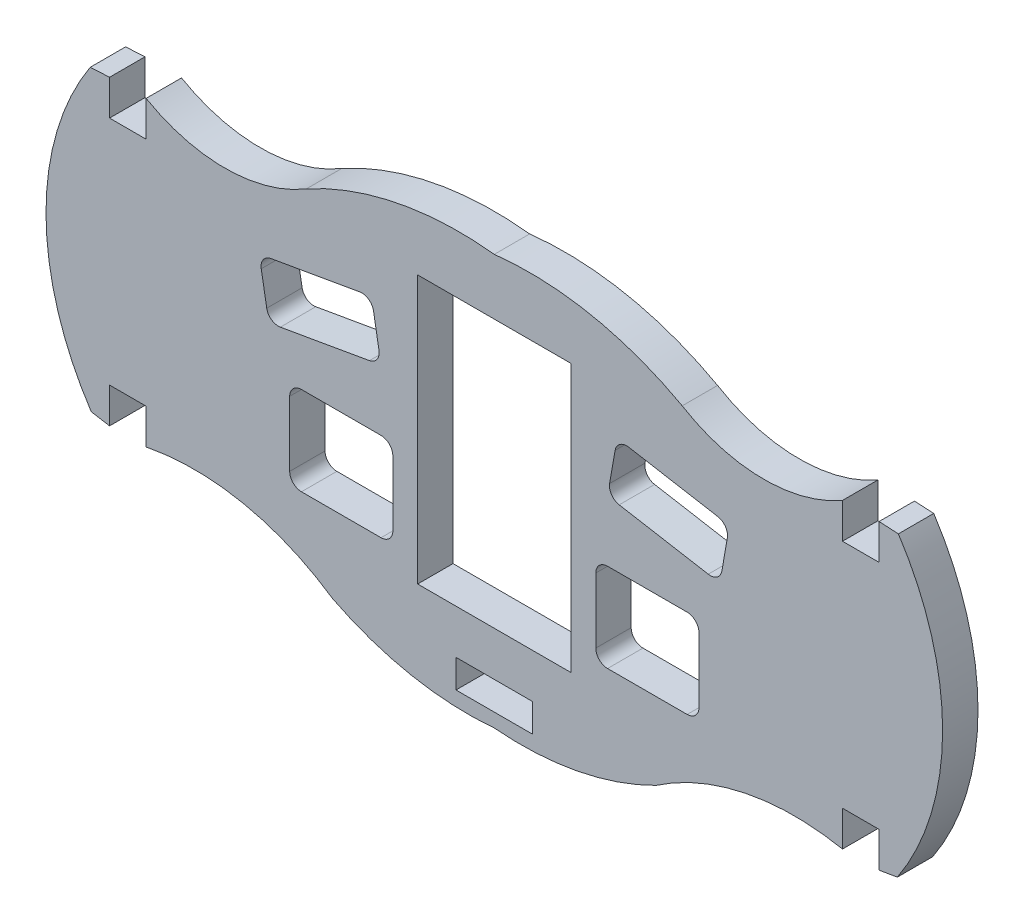
SolidWorks part; units mm, degrees
ref_plane "Front Plane" through (0, 0, 0) normal (0, 0, 1) x (1, 0, 0)
ref_plane "Top Plane" through (0, 0, 0) normal (0, 1, 0) x (1, 0, 0)
ref_plane "Right Plane" through (0, 0, 0) normal (1, 0, 0) x (0, 0, -1)
sketch "Sketch1" plane through (0, 0, 0) normal (0, 0, 1) x (1, 0, 0)
  line L0 (-29.524, 0) -> (29.524, 0) construction
  line L1 (-29.524, -12.802) -> (-29.524, 12.802)
  line L2 (0, 33.6392) -> (0, -30.2413) construction
  line L3 (29.524, -12.802) -> (29.524, 12.802)
  line L4 (-29.524, 9.802) -> (-32.624, 9.802)
  line L5 (-32.624, 9.802) -> (-32.624, 12.802)
  line L6 (-32.624, -9.802) -> (-32.624, -12.802)
  line L7 (-29.524, -9.802) -> (-32.624, -9.802)
  line L8 (32.624, -9.802) -> (32.624, -12.802)
  line L9 (29.524, -9.802) -> (32.624, -9.802)
  line L10 (32.624, 9.802) -> (32.624, 12.802)
  line L11 (29.524, 9.802) -> (32.624, 9.802)
  line L12 (-32.624, -12.802) -> (-34.1749, -12.5392)
  line L13 (-32.624, 12.802) -> (-34.2627, 12.7145)
  line L14 (32.624, -12.802) -> (34.1749, -12.5392)
  line L15 (32.624, 12.802) -> (34.2627, 12.7145)
  line L16 (0, 0) -> (2.992, -10.57) construction
  line L17 (0, 0) -> (-2.992, -10.57) construction
  line L18 (0, 0) -> (2.243, 6.575) construction
  line L19 (0, 0) -> (-2.243, 6.575) construction
  line L20 (0, 0) -> (-16.59, 12.577) construction
  line L21 (0, 0) -> (16.59, 12.577) construction
  line L22 (0, 0) -> (16.293, -14.525) construction
  line L23 (0, 0) -> (-16.293, -14.525) construction
  arc A0 (-34.2627, 12.7145) -> (-34.1749, -12.5392) centre (-15.1087, 0.1541) ccw
  arc A1 (34.2627, 12.7145) -> (34.1749, -12.5392) centre (15.1087, 0.1541) cw
  arc A2 (-29.524, 12.802) -> (-15.9318, 12.9517) centre (-22.8542, 24.3468) ccw
  arc A3 (0, 16.1087) -> (-27.048, 1.347) centre (-2.992, -10.57) ccw
  arc A4 (0, -18.6756) -> (27.048, 1.347) centre (2.243, 6.575) ccw
  arc A5 (27.048, 1.347) -> (0, 16.1087) centre (2.992, -10.57) ccw
  arc A6 (29.524, 12.802) -> (15.9318, 12.9517) centre (22.8542, 24.3468) cw
  arc A7 (-27.048, 1.347) -> (0, -18.6756) centre (-2.243, 6.575) ccw
  arc A8 (-13.7026, -16.037) -> (-29.524, -12.802) centre (-25.4515, -33.1913) ccw
  arc A9 (13.7026, -16.037) -> (29.524, -12.802) centre (25.4515, -33.1913) cw
  point P4 (0, 0)
  point P7 (-29.524, 0)
  dimension "D10" = 45.81
  dimension "D13" = 53.692
  dimension "D14" = 6.575
  dimension "D16" = 12.577
  dimension "D17" = 50.7
  dimension "D19" = 26.666
  dimension "D22" = 41.584
  dimension "D1" = 59.048
  dimension "D2" = 25.604
  dimension "D3" = 3
  dimension "D4" = 3.1
  dimension "D5" = 3
  dimension "D6" = 1.573
  dimension "D7" = 80.384
  dimension "D8" = 1.641
  dimension "D9" = 86.945
  dimension "D11" = 10.57
  dimension "D12" = 2.992
  dimension "D15" = 2.243
  dimension "D18" = 16.59
  dimension "D20" = 14.525
  dimension "D21" = 16.293
extrude "Boss-Extrude1" add sketch "Sketch1" against normal blind 3 contours A4 A9 A5 A6 A3 A2 A7 A8 | A1 L15 L10 L11 L3 L9 L8 L14 | A4 A9 L3 A6 A5 | A8 A7 A3 A2 L1 | L13 A0 L12 L6 L7 L1 L4 L5
sketch "Sketch2" plane through (0, 0, 0) normal (0, 0, 1) x (1, 0, 0)
  line L0 (0, 0) -> (0, -16.3075) construction
  line L1 (-6.5, 11.35) -> (6.5, 11.35)
  line L2 (-6.5, 11.35) -> (-6.5, -11.35)
  line L3 (-6.5, -11.35) -> (6.5, -11.35)
  line L4 (6.5, 11.35) -> (6.5, -11.35)
  line L5 (-6.5, 11.35) -> (6.5, -11.35) construction
  line L6 (-6.5, -11.35) -> (6.5, 11.35) construction
  line L7 (-3.2495, -15.108) -> (3.2495, -15.108)
  line L8 (-3.2495, -15.108) -> (-3.2495, -17.507)
  line L9 (-3.2495, -17.507) -> (3.2495, -17.507)
  line L10 (3.2495, -15.108) -> (3.2495, -17.507)
  line L11 (-3.2495, -15.108) -> (3.2495, -17.507) construction
  line L12 (-3.2495, -17.507) -> (3.2495, -15.108) construction
  line L13 (-14.0066, 0) -> (22.4107, 0) construction
  line L14 (0, 0) -> (0, 15.1397) construction
  line L15 (-9.605, -9.502) -> (-16.351, -9.502)
  line L16 (9.605, -1.991) -> (16.351, -1.991)
  line L17 (8.605, -2.991) -> (8.605, -8.502)
  line L18 (9.605, -9.502) -> (16.351, -9.502)
  line L19 (17.351, -2.991) -> (17.351, -8.502)
  line L20 (-8.605, -2.991) -> (-8.605, -8.502)
  line L21 (-9.605, -1.991) -> (-16.351, -1.991)
  line L22 (-17.351, -2.991) -> (-17.351, -8.502)
  line L23 (10.5901, 3.0091) -> (18.1401, 1.6919)
  line L24 (9.7769, 4.1661) -> (10.242, 6.8319)
  line L25 (19.2971, 2.5051) -> (19.7622, 5.1709)
  line L26 (11.3989, 7.6451) -> (18.9489, 6.3279)
  line L27 (-10.5901, 3.0091) -> (-18.1401, 1.6919)
  line L28 (-9.7769, 4.1661) -> (-10.242, 6.8319)
  line L29 (-11.3989, 7.6451) -> (-18.9489, 6.3279)
  line L30 (-19.2971, 2.5051) -> (-19.7622, 5.1709)
  arc A0 (8.605, -8.502) -> (9.605, -9.502) centre (9.605, -8.502) ccw
  arc A1 (16.351, -9.502) -> (17.351, -8.502) centre (16.351, -8.502) ccw
  arc A2 (16.351, -1.991) -> (17.351, -2.991) centre (16.351, -2.991) cw
  arc A3 (9.605, -1.991) -> (8.605, -2.991) centre (9.605, -2.991) ccw
  arc A4 (-8.605, -8.502) -> (-9.605, -9.502) centre (-9.605, -8.502) cw
  arc A5 (-9.605, -1.991) -> (-8.605, -2.991) centre (-9.605, -2.991) cw
  arc A6 (-16.351, -1.991) -> (-17.351, -2.991) centre (-16.351, -2.991) ccw
  arc A7 (-16.351, -9.502) -> (-17.351, -8.502) centre (-16.351, -8.502) cw
  arc A8 (9.7769, 4.1661) -> (10.5901, 3.0091) centre (10.762, 3.9942) ccw
  arc A9 (18.1401, 1.6919) -> (19.2971, 2.5051) centre (18.3119, 2.677) ccw
  arc A10 (19.7622, 5.1709) -> (18.9489, 6.3279) centre (18.777, 5.3428) ccw
  arc A11 (10.242, 6.8319) -> (11.3989, 7.6451) centre (11.2271, 6.66) cw
  arc A12 (-9.7769, 4.1661) -> (-10.5901, 3.0091) centre (-10.762, 3.9942) cw
  arc A13 (-10.242, 6.8319) -> (-11.3989, 7.6451) centre (-11.2271, 6.66) ccw
  arc A14 (-19.7622, 5.1709) -> (-18.9489, 6.3279) centre (-18.777, 5.3428) cw
  arc A15 (-18.1401, 1.6919) -> (-19.2971, 2.5051) centre (-18.3119, 2.677) cw
  point P0 (0, 0)
  point P6 (0, -16.3075)
  point P23 (8.605, -9.502)
  point P26 (17.351, -9.502)
  point P29 (17.351, -1.991)
  point P32 (8.605, -1.991)
  point P48 (9.605, 3.181)
  point P53 (19.1252, 1.52)
  point P56 (19.934, 6.156)
  point P59 (10.4138, 7.817)
  dimension "D10" = 1
  dimension "D16" = 1
  dimension "D1" = 13
  dimension "D2" = 22.7
  dimension "D3" = 6.499
  dimension "D4" = 2.399
  dimension "D5" = 3.758
  dimension "D6" = 2.105
  dimension "D7" = 1.991
  dimension "D8" = 7.511
  dimension "D9" = 8.746
  dimension "D11" = 3.181
  dimension "D12" = 3.105
  dimension "D13" = 9.664
  dimension "D14" = 4.706
  dimension "D15" = 6.156
extrude "Cut-Extrude1" cut sketch "Sketch2" against normal blind 3 contours A15 L27 A12 L28 A13 L29 A14 L30 | L4 L1 L2 L3 | A7 L15 A4 L20 A5 L21 A6 L22 | L16 A3 L17 A0 L18 A1 L19 A2 | A11 L24 A8 L23 A9 L25 A10 L26 | L10 L7 L8 L9
